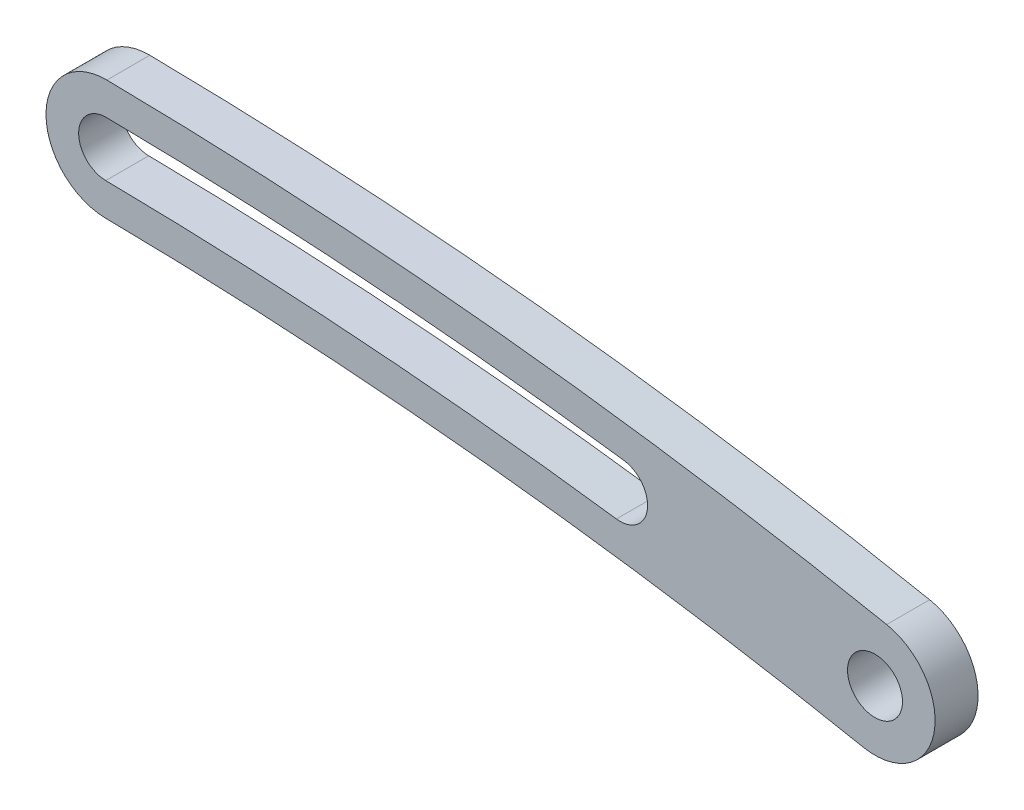
SolidWorks part; units mm, degrees
material "Thornel Mat VMA"
ref_plane "Front Plane" through (0, 0, 0) normal (0, 0, 1) x (1, 0, 0)
ref_plane "Top Plane" through (0, 0, 0) normal (0, 1, 0) x (1, 0, 0)
ref_plane "Right Plane" through (0, 0, 0) normal (1, 0, 0) x (0, 0, -1)
sketch "Sketch1" plane through (0, 0, 0) normal (0, 0, 1) x (1, 0, 0)
  circle A0 centre (6.1117, 112.285) radius 1.6
  circle A1 centre (6.1117, 112.285) radius 3.5
  arc A2 (6.7923, 115.7182) -> (-38.5986, 120.4698) centre (-41.8232, -129.5094) ccw
  arc A3 (5.4311, 108.8518) -> (-38.6889, 113.4704) centre (-41.8232, -129.5094) ccw
  arc A4 (-38.5986, 120.4698) -> (-38.6889, 113.4704) centre (-38.6438, 116.9701) ccw
  circle A5 centre (-38.6438, 116.9701) radius 1.6
  arc A6 (-38.6231, 118.57) -> (6.4228, 113.8544) centre (-41.8232, -129.5094) cw
  arc A7 (-38.6644, 115.3703) -> (5.8005, 110.7155) centre (-41.8232, -129.5094) cw
  arc A8 (-8.5106, 116.344) -> (-8.9402, 113.173) centre (-8.7254, 114.7585) cw
  dimension "D1" = 3.2
  dimension "D2" = 7
  dimension "D5" = 250
  dimension "D3" = 30
  dimension "D4" = 45
extrude "Boss-Extrude1" add sketch "Sketch1" along normal blind 2.5 contours A7 A5 A6 A1 A2 A4 A3 | A7 A1 A6 A0 | A6 A8 A7 A1 | A1 A7 A0 A6
